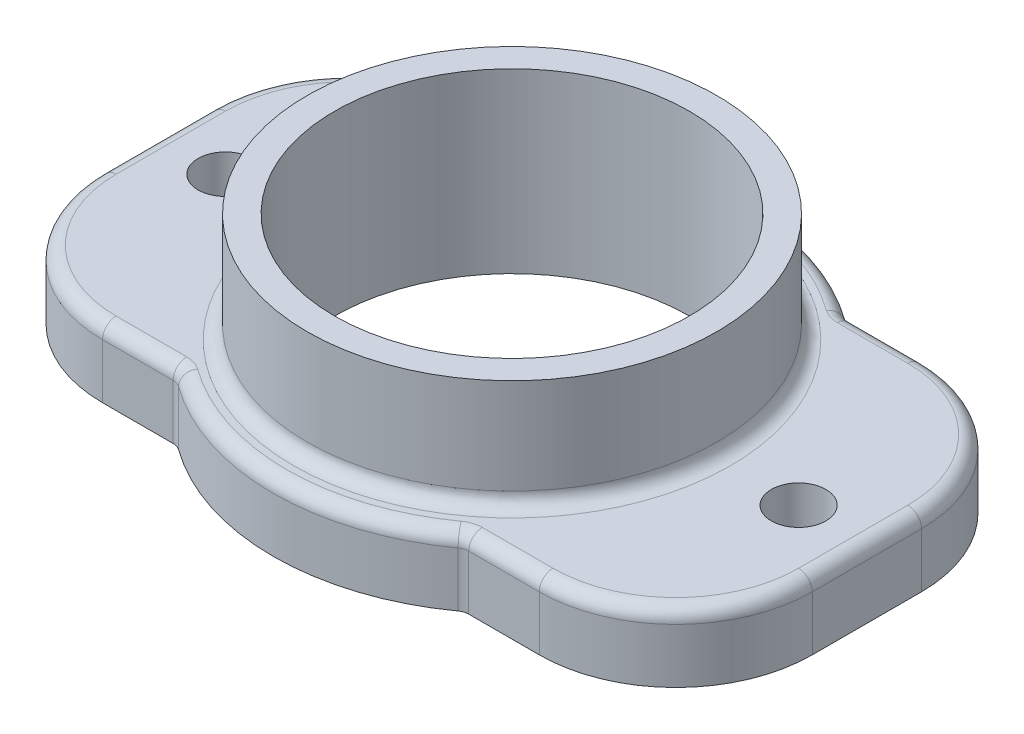
SolidWorks part; units mm, degrees
ref_plane "前基準面" through (0, 0, 0) normal (0, 0, 1) x (1, 0, 0)
ref_plane "上基準面" through (0, 0, 0) normal (0, 1, 0) x (1, 0, 0)
ref_plane "右基準面" through (0, 0, 0) normal (1, 0, 0) x (0, 0, -1)
sketch "草圖1" plane through (0, 0, 0) normal (0, 1, 0) x (1, 0, 0)
  line L0 (26, -14) -> (-26, 14) construction
  line L1 (-26, 14) -> (26, 14)
  line L2 (-26, 14) -> (-26, -14)
  line L3 (-26, -14) -> (26, -14)
  line L4 (26, 14) -> (26, -14)
  dimension "D1" = 52
  dimension "D2" = 28
extrude "填料-伸長1" add sketch "草圖1" along normal blind 5
sketch "草圖2" plane through (0, 0, 0) normal (0, 1, 0) x (1, 0, 0)
  circle A0 centre (0, 0) radius 17.5
  dimension "D1" = 35
extrude "填料-伸長2" add sketch "草圖2" along normal blind 5
sketch "草圖3" plane through (0, 5, 0) normal (0, 1, 0) x (1, 0, 0)
  circle A0 centre (0, 0) radius 15
  dimension "D1" = 30
extrude "填料-伸長3" add sketch "草圖3" along normal blind 8
sketch "草圖4" plane through (0, 13, 0) normal (0, 1, 0) x (1, 0, 0)
  circle A0 centre (0, 0) radius 13
  dimension "D1" = 26
extrude "除料-伸長1" cut sketch "草圖4" against normal through all
fillet "圓角1" radius 10 4 edges at (26, 2.5, -14) (26, 2.5, 14) (-26, 2.5, 14) (-26, 2.5, -14)
sketch "草圖5" plane through (0, 0, 0) normal (0, -1, 0) x (1, 0, 0)
  line L0 (-26, -4) -> (-26, 4) construction
  line L1 (-21, 0) -> (0, 0) construction
  circle A0 centre (-21, 0) radius 2
  dimension "D1" = 4
  dimension "D2" = 5
extrude "除料-伸長2" cut sketch "草圖5" against normal through all
mirror "鏡射1" about plane through (0, 0, 0) normal (1, 0, 0) of "除料-伸長2"
fillet "圓角2" radius 1 1 edges at (0, 5, 15)
fillet "圓角3" radius 1 4 edges at (-10.5, 2.5, -14) (10.5, 2.5, -14) (10.5, 2.5, 14) (-10.5, 2.5, 14)
fillet "圓角4" radius 1 16 edges at (-10.5206, 5, -14.0485) (0, 5, -17.5) (10.5206, 5, -14.0485) (13.4141, 5, -14) (23.0711, 5, -11.0711) (26, 5, 0) (23.0711, 5, 11.0711) (13.4141, 5, 14) (10.5206, 5, 14.0485) (0, 5, 17.5) (-10.5206, 5, 14.0485) (-13.4141, 5, 14) (-23.0711, 5, 11.0711) (-26, 5, 0) (-23.0711, 5, -11.0711) (-13.4141, 5, -14)
